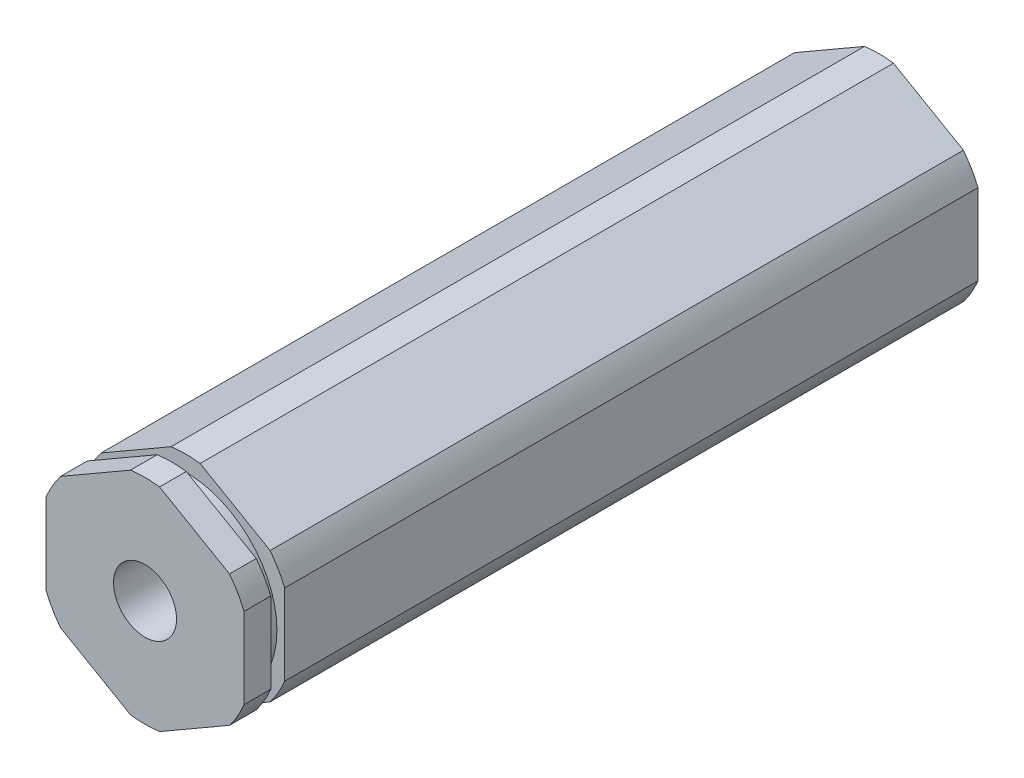
SolidWorks part; units mm, degrees
ref_plane "Front Plane" through (0, 0, 0) normal (0, 0, 1) x (1, 0, 0)
ref_plane "Top Plane" through (0, 0, 0) normal (0, 1, 0) x (1, 0, 0)
ref_plane "Right Plane" through (0, 0, 0) normal (1, 0, 0) x (0, 0, -1)
sketch "Sketch1" plane through (0, 0, 0) normal (0, 0, 1) x (1, 0, 0)
  line L1 (0, 7.3323) -> (-6.35, 3.6662)
  line L2 (-6.35, 3.6662) -> (-6.35, -3.6662)
  line L3 (-6.35, -3.6662) -> (0, -7.3323)
  line L4 (0, -7.3323) -> (6.35, -3.6662)
  line L5 (6.35, -3.6662) -> (6.35, 3.6662)
  line L6 (6.35, 3.6662) -> (0, 7.3323)
  circle A0 centre (0, 0) radius 6.35 construction
  circle A1 centre (0, 0) radius 6.858
  dimension "D1" = 12.7
  dimension "D2" = 13.716
extrude "Boss-Extrude1" add sketch "Sketch1" along normal mid plane 47.0662 contours L5 A1 L6 L1 L2 L3 L4
sketch "Sketch6" plane through (0, 0, 0) normal (0, 0, 1) x (1, 0, 0)
  line L0 (5.4183, 4.2041) -> (0.9317, 6.7944) construction
  circle A0 centre (0, 0) radius 6.35
hole_wizard "#10-32 Tapped Hole1" positions "3DSketch1" profile "Sketch2" tap size "#10-32" standard "ANSI Inch"
sketch3d "3DSketch1"
  line L0 (0, 0, 23.5331) -> (0, 0, -23.5331) construction
  line L1 (0, 0, 23.5331) -> (0, 0, -23.5331) construction
  point P0 (0, 0, 23.5331)
  point P4 (0, 0, -23.5331)
sketch "Sketch2" plane through (0, 0, 23.5331) normal (1, 0, 0) x (0, -1, 0)
  line L0 (0, 0) -> (0, 17.5608)
  line L1 (0, 17.5608) -> (2.0193, 16.3474)
  line L2 (2.0193, 16.3474) -> (2.0193, 0)
  line L5 (2.0193, 0) -> (0, 0)
  line L10 (0, 17.5608) -> (-2.0193, 16.3474) construction
  line L11 (0, -6.35) -> (0, 107.95) construction
  dimension "Tap Drill Dia." = 4.0386
  dimension "Tap Drill Depth" = 16.3474
  dimension "Drill Angle" = 118
cosmetic thread "Hole Thread1" parameters "D1"=13.97, "D2"=4.826
cosmetic thread "Hole Thread2" parameters "D1"=13.97, "D2"=4.826
sketch "Sketch5" plane through (0, 0, 0) normal (1, 0, 0) x (0, 0, -1)
  line L0 (23.5331, 6.858) -> (-23.5331, 6.858) construction
  line L1 (-21.8186, 6.858) -> (-20.9296, 6.858)
  line L2 (-21.8186, 6.858) -> (-21.8186, 5.8547)
  line L3 (-21.8186, 5.8547) -> (-20.9296, 5.8547)
  line L4 (-20.9296, 6.858) -> (-20.9296, 5.8547)
  line L5 (-165.0472, 0) -> (-158.8423, 0) construction
  dimension "D1" = 5.8547
  dimension "D2" = 0.889
  dimension "D3" = 1.7145
revolve "Cut-Revolve1" cut sketch "Sketch5" angle 360 about L5
